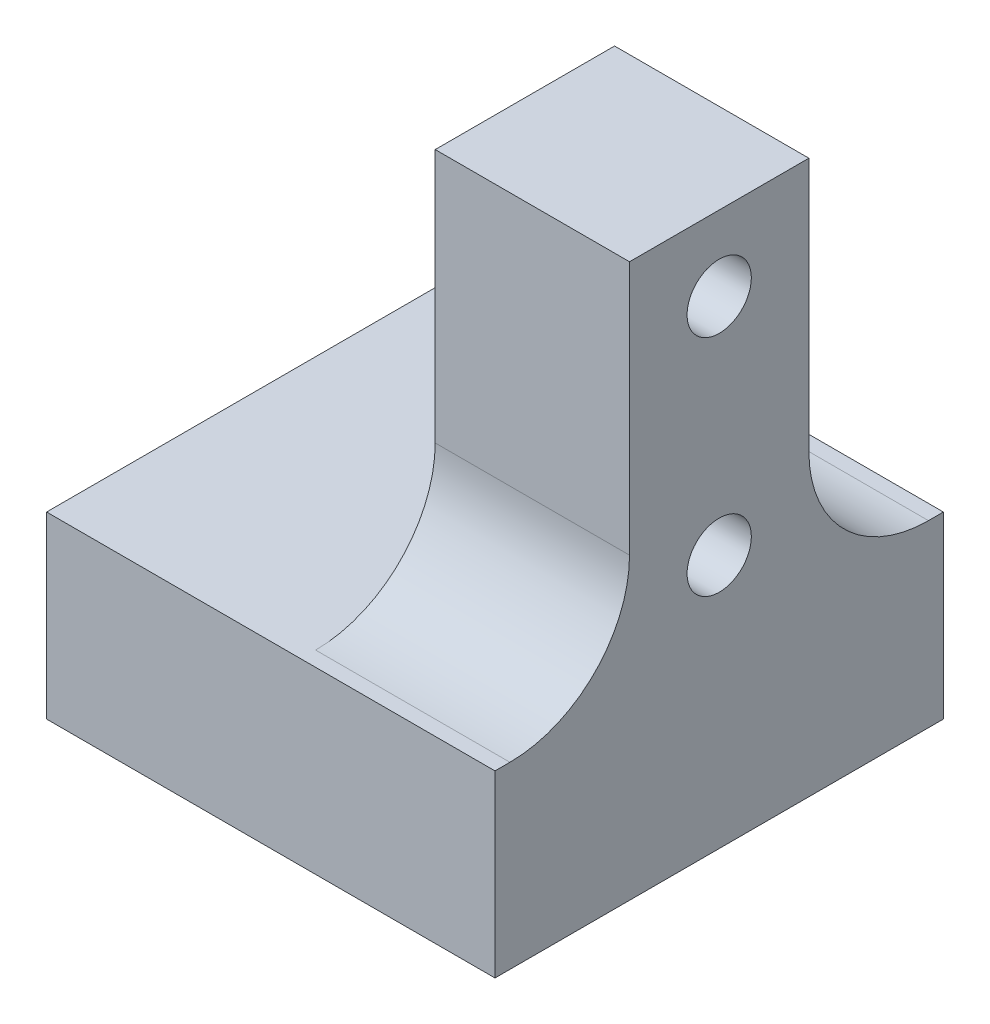
SolidWorks part; units mm, degrees
ref_plane "Front Plane" through (0, 0, 0) normal (0, 0, 1) x (1, 0, 0)
ref_plane "Top Plane" through (0, 0, 0) normal (0, 1, 0) x (1, 0, 0)
ref_plane "Right Plane" through (0, 0, 0) normal (1, 0, 0) x (0, 0, -1)
sketch "Sketch1" plane through (0, 0, 0) normal (0, 1, 0) x (1, 0, 0)
  line L1 (15, -15) -> (-15, -15)
  line L2 (15, -15) -> (15, 15)
  line L3 (15, 15) -> (-15, 15)
  line L4 (-15, -15) -> (-15, 15)
  line L5 (15, -15) -> (-15, 15) construction
  line L6 (15, 15) -> (-15, -15) construction
  point P0 (0, 0)
  dimension "D1" = 30
extrude "Boss-Extrude1" add sketch "Sketch1" along normal blind 12
sketch "Sketch2" plane through (0, 12, 0) normal (0, 1, 0) x (1, 0, 0)
  line L0 (-9.3187, 0) -> (15, 0) construction
  line L1 (15, -15) -> (15, 15) construction
  line L2 (0, 15) -> (0, -10.2191) construction
  line L3 (15, 15) -> (-15, 15) construction
  line L5 (15, -6) -> (10, -6)
  line L6 (15, -6) -> (15, 6)
  line L7 (15, 6) -> (10, 6)
  line L8 (10, -6) -> (10, 6)
  line L9 (10, 6) -> (2, 6)
  line L10 (10, 6) -> (10, -6)
  line L11 (10, -6) -> (2, -6)
  line L12 (2, 6) -> (2, -6)
  line M8 (15, -15) -> (15, 15)
  dimension "D1" = 5
  dimension "D2" = 12
  dimension "D3" = 8
extrude "Boss-Extrude2" add sketch "Sketch2" along normal blind 25 contours L8 L5 L7 M8 | L10 L9 L12 L11
fillet "Fillet1" radius 8 2 edges at (8.5, 12, -6) (8.5, 12, 6)
sketch "Sketch3" plane through (15, 0, 0) normal (1, 0, 0) x (0, 0, -1)
  line L0 (0, 0) -> (0, 37) construction
  line L1 (-6, 37) -> (6, 37) construction
  line L4 (14, 12) -> (15, 12) construction
  circle A0 centre (0, 17) radius 2.15
  circle A1 centre (0, 32) radius 2.15
  point P9 (0, 0)
  point P10 (0, 14.518)
  dimension "D3" = 4.3
  dimension "D1" = 15
  dimension "D2" = 5
extrude "Cut-Extrude1" cut sketch "Sketch3" against normal through all
